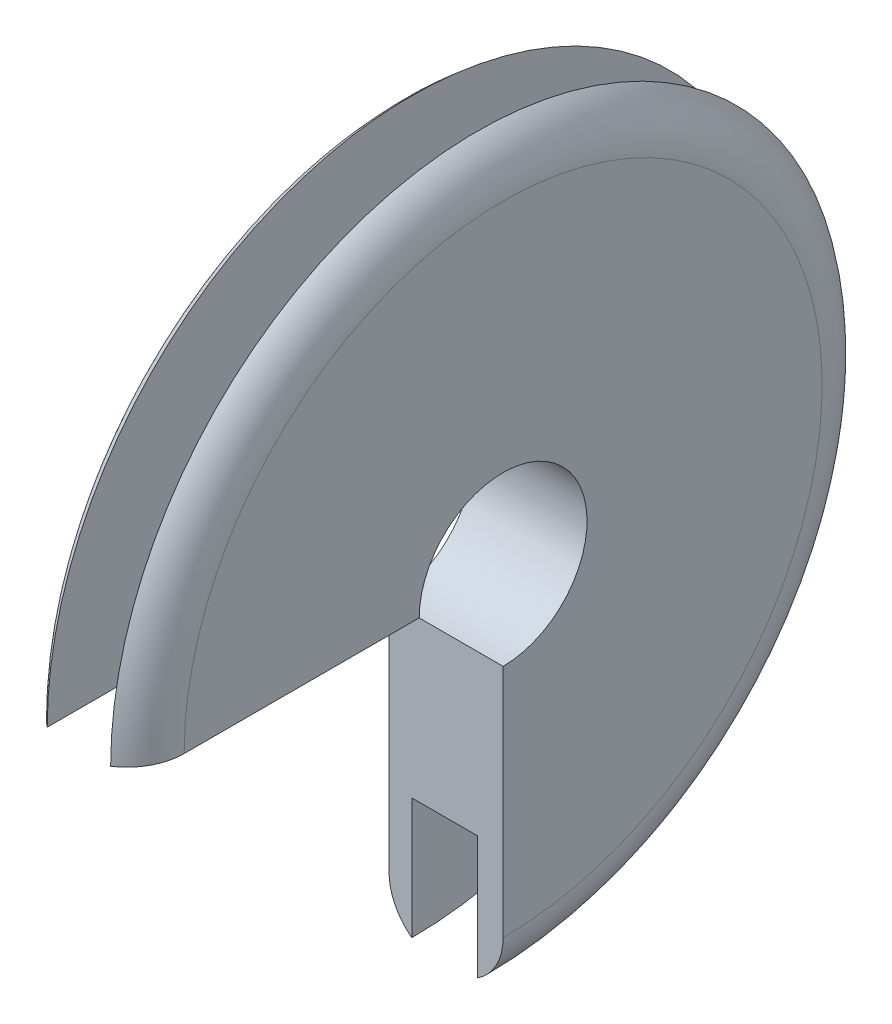
SolidWorks part; units mm, degrees
ref_plane "Front Plane" through (0, 0, 0) normal (0, 0, 1) x (1, 0, 0)
ref_plane "Top Plane" through (0, 0, 0) normal (0, 1, 0) x (1, 0, 0)
ref_plane "Right Plane" through (0, 0, 0) normal (1, 0, 0) x (0, 0, -1)
sketch "Sketch1" plane through (0, 0, 0) normal (0, 1, 0) x (1, 0, 0)
  line L0 (-161.2788, 0) -> (168.1608, 0) construction
  line L1 (0, 103.9784) -> (0, -116.8448) construction
  line L4 (-13.5942, 76.0174) -> (-13.5942, 20)
  line L5 (-13.5942, 20) -> (13.5942, 20)
  line L6 (13.5942, 76.0174) -> (13.5942, 20)
  line L7 (-13.5942, 76.0174) -> (13.5942, 20) construction
  line L8 (-13.5942, 20) -> (13.5942, 76.0174) construction
  arc A0 (-13.5942, 76.0174) -> (13.5942, 76.0174) centre (0, 76.0174) cw
  point P5 (0, 48.0087)
  dimension "D1" = 20
revolve "Revolve1" add sketch "Sketch1" angle 180 about L0
sketch "Sketch7" plane through (0, 0, 0) normal (0, 0, 1) x (1, 0, 0)
  line L0 (-109.3221, 0) -> (92.6398, 0) construction
  line L1 (-8.1637, 104.5304) -> (7.4538, 104.5304)
  line L2 (-8.1637, 104.5304) -> (-8.1637, 58.033)
  line L3 (-8.1637, 58.033) -> (7.4538, 58.033)
  line L4 (7.4538, 104.5304) -> (7.4538, 58.033)
revolve "Cut-Revolve1" cut sketch "Sketch7" angle 360 about L0
